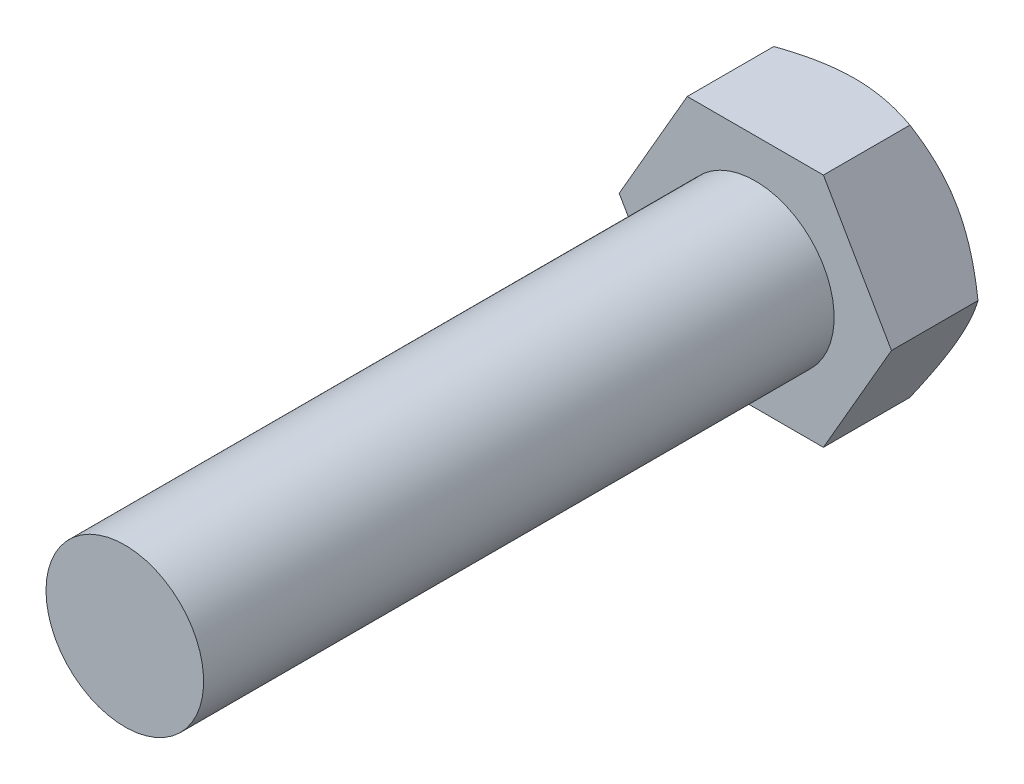
SolidWorks part; units mm, degrees
ref_plane "Alzado" through (0, 0, 0) normal (0, 0, 1) x (1, 0, 0)
ref_plane "Planta" through (0, 0, 0) normal (0, 1, 0) x (1, 0, 0)
ref_plane "Vista lateral" through (0, 0, 0) normal (1, 0, 0) x (0, 0, -1)
sketch "Croquis1" plane through (0, 0, 0) normal (0, 0, 1) x (1, 0, 0)
  line L1 (16.4545, 0) -> (8.2272, 14.25)
  line L2 (8.2272, 14.25) -> (-8.2272, 14.25)
  line L3 (-8.2272, 14.25) -> (-16.4545, 0)
  line L4 (-16.4545, 0) -> (-8.2272, -14.25)
  line L5 (-8.2272, -14.25) -> (8.2272, -14.25)
  line L6 (8.2272, -14.25) -> (16.4545, 0)
  circle A0 centre (0, 0) radius 14.25 construction
  dimension "D1" = 28.5
extrude "Saliente-Extruir1" add sketch "Croquis1" along normal blind 12
sketch "Croquis2" plane through (0, 0, 12) normal (0, 0, 1) x (1, 0, 0)
  circle A0 centre (0, 0) radius 9.525
  dimension "D1" = 19.05
extrude "Saliente-Extruir2" add sketch "Croquis2" along normal blind 76.2
sketch "Croquis3" plane through (0, 0, 0) normal (0, 0, -1) x (-1, 0, 0)
  circle A0 centre (0, 0) radius 14.25
  circle A1 centre (0, 0) radius 38.9
extrude "Cortar-Extruir1" cut sketch "Croquis3" against normal blind 30 draft 55
